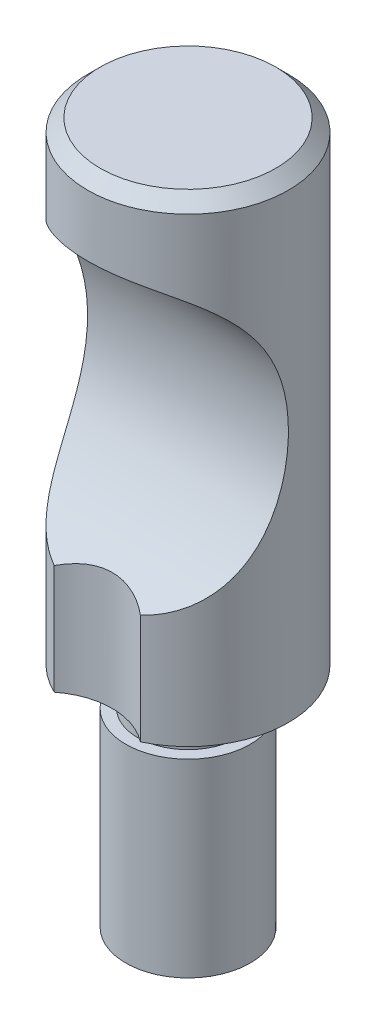
SolidWorks part; units mm, degrees
material "AISI 4340 Steel, normalized"
ref_plane "Front Plane" through (0, 0, 0) normal (0, 0, 1) x (1, 0, 0)
ref_plane "Top Plane" through (0, 0, 0) normal (0, 1, 0) x (1, 0, 0)
ref_plane "Right Plane" through (0, 0, 0) normal (1, 0, 0) x (0, 0, -1)
sketch "Sketch1" plane through (0, 0, 0) normal (0, 0, 1) x (1, 0, 0)
  line L0 (0, 0) -> (0, 55.5) construction
  line L1 (0, 55.5) -> (7.95, 55.5)
  line L7 (4.925, 0) -> (0, 0)
  line L8 (0, 0) -> (0, 55.5)
  line L9 (7.95, 55.5) -> (7.95, 18)
  line L10 (7.95, 18) -> (4, 18)
  line L11 (4, 18) -> (4, 15)
  line L12 (4, 15) -> (4.925, 15)
  line L14 (4.925, 15) -> (4.925, 0)
  dimension "D1" = 55.5
  dimension "D2" = 7.95
  dimension "D3" = 4.925
  dimension "D4" = 15
  dimension "D5" = 4
  dimension "D6" = 3
revolve "Revolve1" add sketch "Sketch1" angle 360 about L0
cosmetic thread "Cosmetic Thread1" parameters "D2"=6.891
sketch "Sketch2" plane through (0, 0, 0) normal (1, 0, 0) x (0, 0, -1)
  line L0 (-7.95, 18) -> (7.95, 18) construction
  circle A0 centre (-12.5, 38) radius 12.5
  point P5 (0, 0)
  point P7 (31.7133, 19.956)
  dimension "D1" = 25
  dimension "D2" = 20
  dimension "D3" = 12.5
extrude "Cut-Extrude1" cut sketch "Sketch2" against normal up to next and the other way up to next
sketch "Sketch3" plane through (0, 18, 0) normal (0, -1, 0) x (1, 0, 0)
  circle A0 centre (0, 11.5) radius 5.5
  point P2 (0, 0)
  dimension "D1" = 11
  dimension "D2" = 11.5
extrude "Cut-Extrude2" cut sketch "Sketch3" against normal up to next
chamfer "Chamfer1" distance 1 angle 45 1 edges at (0, 55.5, -7.95)
